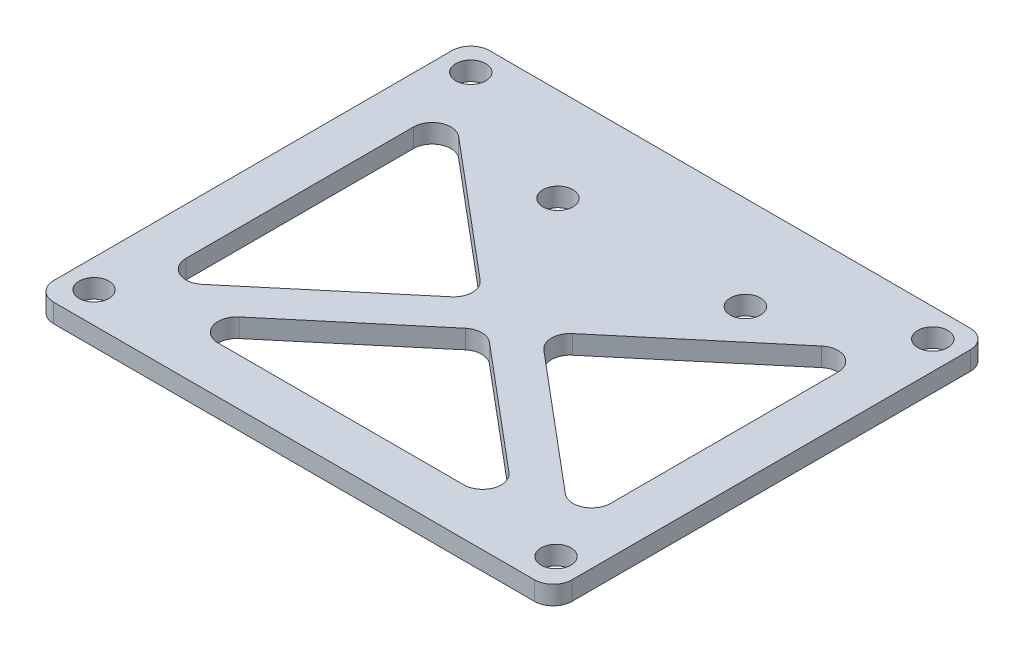
SolidWorks part; units mm, degrees
material "碳板"
ref_plane "前视基准面" through (0, 0, 0) normal (0, 0, 1) x (1, 0, 0)
ref_plane "上视基准面" through (0, 0, 0) normal (0, 1, 0) x (1, 0, 0)
ref_plane "右视基准面" through (0, 0, 0) normal (1, 0, 0) x (0, 0, -1)
sketch "草图1" plane through (0, 0, 0) normal (0, 1, 0) x (1, 0, 0)
  line L0 (24.65, 20.25) -> (-24.65, 20.25) construction
  line L1 (-27.65, 23.25) -> (27.65, 23.25)
  line L2 (-27.65, 23.25) -> (-27.65, -23.25)
  line L3 (-27.65, -23.25) -> (27.65, -23.25)
  line L4 (27.65, 23.25) -> (27.65, -23.25)
  line L5 (-27.65, 23.25) -> (27.65, -23.25) construction
  line L6 (-27.65, -23.25) -> (27.65, 23.25) construction
  line L7 (24.65, 20.25) -> (24.65, -19.95) construction
  line L8 (0, 35.2418) -> (0, -35.2898) construction
  line L9 (-39.997, 0) -> (30.8454, 0) construction
  line L10 (-3.1076, 0) -> (-22.65, 16.4326)
  line L11 (-22.65, 16.4326) -> (-22.65, -16.4326)
  line L12 (0, -2.6131) -> (-18.5962, -18.25)
  line L13 (-18.5962, -18.25) -> (18.5962, -18.25)
  line L14 (-3.1076, 0) -> (-22.65, -16.4326)
  line L15 (0, -2.6131) -> (18.5962, -18.25)
  line L16 (3.1076, 0) -> (22.65, 16.4326)
  line L17 (3.1076, 0) -> (22.65, -16.4326)
  line L18 (22.65, 16.4326) -> (22.65, -16.4326)
  circle A0 centre (11.65, 13.25) radius 1.6
  circle A1 centre (-8.35, 13.25) radius 1.6
  circle A2 centre (24.65, 20.25) radius 1.6
  circle A3 centre (-24.65, 20.25) radius 1.6
  circle A4 centre (-24.65, -19.95) radius 1.6
  circle A5 centre (24.65, -19.95) radius 1.6
  point P0 (0, 0)
  point P32 (-22.65, 0)
  point P33 (0, -18.25)
  dimension "D3" = 3.2
  dimension "D6" = 20
  dimension "D7" = 3.2
  dimension "D1" = 46.5
  dimension "D2" = 55.3
  dimension "D4" = 16
  dimension "D5" = 10
  dimension "D8" = 3
  dimension "D11" = 49.3
  dimension "D12" = 40.2
  dimension "D13" = 3
  dimension "D14" = 5
  dimension "D15" = 2
  dimension "D16" = 2
  dimension "D17" = 5
  dimension "D9" = 2
  dimension "D10" = 2
extrude "凸台-拉伸1" add sketch "草图1" along normal blind 2
fillet "圆角1" radius 2 13 edges at (22.65, 1, -16.4326) (3.1076, 1, 0) (22.65, 1, 16.4326) (-18.5962, 1, 18.25) (18.5962, 1, 18.25) (0, 1, 2.6131) (-22.65, 1, -16.4326) (-22.65, 1, 16.4326) (-3.1076, 1, 0) (-27.65, 1, 23.25) (-27.65, 1, -23.25) (27.65, 1, -23.25) (27.65, 1, 23.25)
